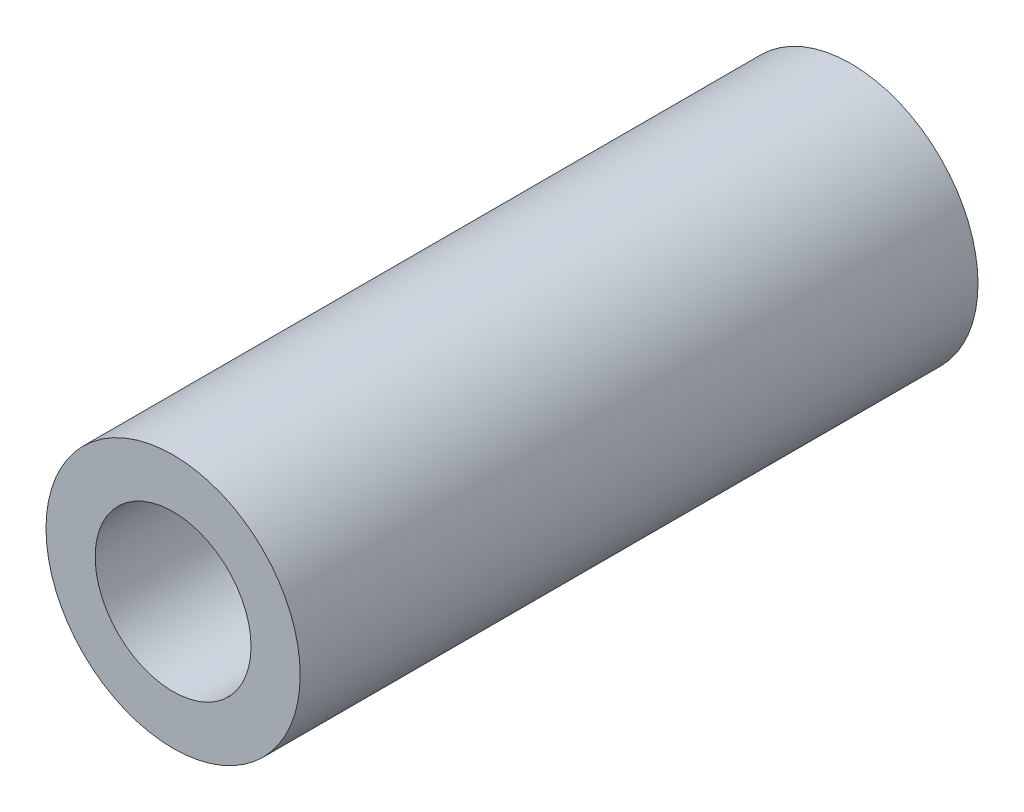
SolidWorks part; units mm, degrees
material "6061-T6 (SS)"
ref_plane "Front Plane" through (0, 0, 0) normal (0, 0, 1) x (1, 0, 0)
ref_plane "Top Plane" through (0, 0, 0) normal (0, 1, 0) x (1, 0, 0)
ref_plane "Right Plane" through (0, 0, 0) normal (1, 0, 0) x (0, 0, -1)
sketch "Sketch1" plane through (0, 0, 0) normal (0, 0, 1) x (1, 0, 0)
  circle A0 centre (0, 0) radius 2.3813
  circle A1 centre (0, 0) radius 1.4605
  dimension "OD" = 4.7625
  dimension "ID" = 2.921
extrude "Extrude1" add sketch "Sketch1" along normal mid plane 12.7
sketch "Sketch2" plane through (0, 0, 0) normal (1, 0, 0) x (0, 0, -1)
  line L0 (-6.35, -1.4605) -> (6.35, -1.4605) construction
  line L3 (6.35, 1.4605) -> (-6.35, 1.4605) construction
  line L5 (-6.35, -1.4605) -> (6.35, -1.4605)
  line L6 (6.35, 1.4605) -> (-6.35, 1.4605)
sketch "Sketch4" plane through (0, 0, 6.35) normal (0, 0, 1) x (1, 0, 0)
  line L0 (0, 0) -> (-1.0327, 1.0327)
  line L1 (0, -2.1828) -> (0, 2.1828) construction
  circle A0 centre (0, 0) radius 1.4605 construction
  dimension "D1" = 45
